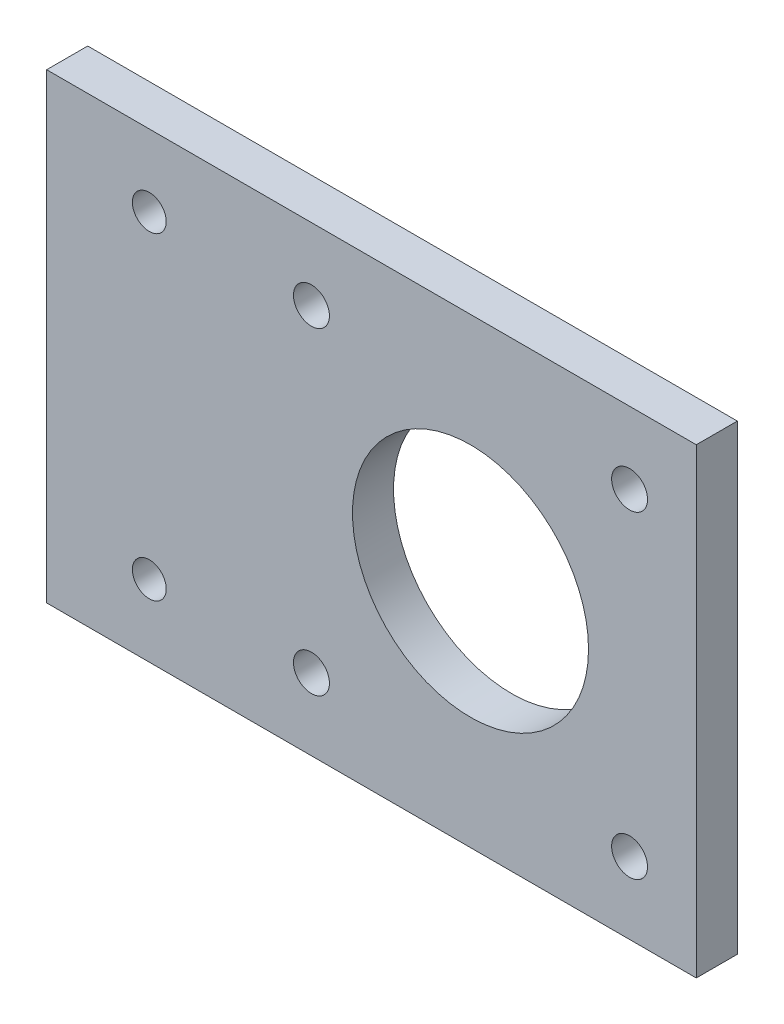
SolidWorks part; units mm, degrees
ref_plane "Plano frontal" through (0, 0, 0) normal (0, 0, 1) x (1, 0, 0)
ref_plane "Plano superior" through (0, 0, 0) normal (0, 1, 0) x (1, 0, 0)
ref_plane "Plano direito" through (0, 0, 0) normal (1, 0, 0) x (0, 0, -1)
sketch "Esboço1" plane through (0, 0, 0) normal (0, 0, 1) x (1, 0, 0)
  line L0 (-41.3, 0) -> (-25.3872, 0) construction
  line L1 (-15.5, 15.5) -> (15.5, 15.5) construction
  line L2 (-15.5, 15.5) -> (-15.5, -15.5) construction
  line L3 (-15.5, -15.5) -> (15.5, -15.5) construction
  line L4 (15.5, 15.5) -> (15.5, -15.5) construction
  line L5 (-15.5, 15.5) -> (15.5, -15.5) construction
  line L6 (-15.5, -15.5) -> (15.5, 15.5) construction
  line L7 (22, 22.5) -> (-41.3, 22.5)
  line L8 (22, 22.5) -> (22, -22.5)
  line L9 (22, -22.5) -> (-41.3, -22.5)
  line L10 (-41.3, 22.5) -> (-41.3, -22.5)
  line L11 (-21.3, -22.5) -> (-21.3, 22.5) construction
  circle A0 centre (0, 0) radius 11.5
  circle A1 centre (-15.5, 15.5) radius 1.75
  circle A2 centre (15.5, 15.5) radius 1.75
  circle A3 centre (15.5, -15.5) radius 1.75
  circle A4 centre (-15.5, -15.5) radius 1.75
  circle A5 centre (-31.3, -15.5) radius 1.65
  circle A6 centre (-31.3, 15.5) radius 1.65
  point P16 (22, 0)
  dimension "D1" = 3.5
  dimension "D2" = 23
  dimension "D7" = 3.3
  dimension "D3" = 31
  dimension "D4" = 45
  dimension "D5" = 22
  dimension "D6" = 21.3
  dimension "D8" = 20
  dimension "D9" = 10
  dimension "D10" = 31
extrude "Ressalto-extrusão1" add sketch "Esboço1" along normal blind 25
sketch "Esboço2" plane through (0, 0, 0) normal (0, 1, 0) x (1, 0, 0)
  line L0 (22, -4) -> (-23, -4)
  line L1 (22, -25) -> (22, 0) construction
  line L2 (-28, -4) -> (-28, -25)
  line L3 (22, -25) -> (-41.3, -25) construction
  line L4 (-23, -25) -> (22, -4)
  line L5 (-41.3, -4) -> (-23, -4)
  line L6 (-41.3, -25) -> (-41.3, 0) construction
  line L8 (22, 0) -> (-41.3, 0) construction
  line L9 (-41.3, -4) -> (-41.3, -25)
  line L10 (-41.3, -25) -> (-23, -25)
  line L11 (-23, -25) -> (22, -25)
  line L12 (22, -25) -> (22, -4)
  dimension "D1" = 4
  dimension "D2" = 45
  dimension "D3" = 5
extrude "Corte-extrusão1" cut sketch "Esboço2" against normal through all both and the other way through all
